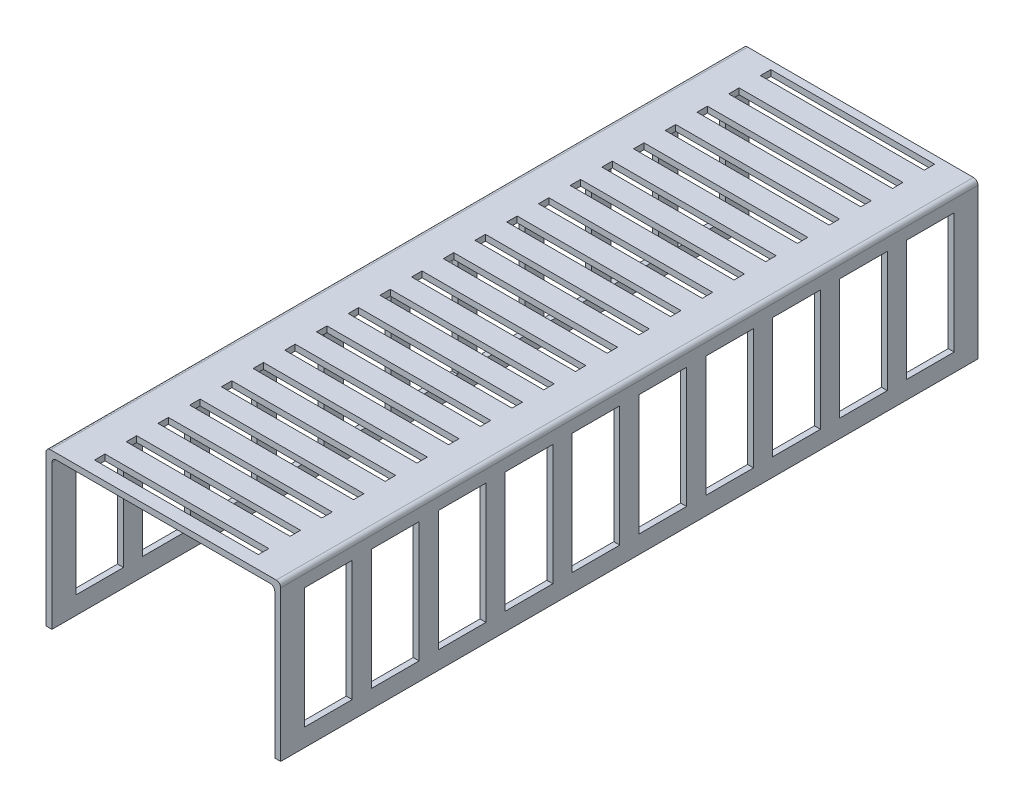
SolidWorks part; units mm, degrees
material "Nylon 101"
ref_plane "Front Plane" through (0, 0, 0) normal (0, 0, 1) x (1, 0, 0)
ref_plane "Top Plane" through (0, 0, 0) normal (0, 1, 0) x (1, 0, 0)
ref_plane "Right Plane" through (0, 0, 0) normal (1, 0, 0) x (0, 0, -1)
sketch "Sketch2" plane through (0, 16100.0493, 0) normal (0, 1, 0) x (1, 0, 0)
  line L0 (-34.7, 120.7548) -> (-34.7, 117.2548)
  line L5 (-34.7, 117.2548) -> (20.3, 117.2548)
  line L6 (-34.7, 120.7548) -> (20.3, 120.7548)
  line L7 (20.3, 120.7548) -> (20.3, 117.2548)
  line L9 (-46.6, 134.05) -> (32.2, 134.05)
  line L10 (-46.6, 134.05) -> (-46.6, -100.05)
  line L11 (-46.6, -100.05) -> (32.2, -100.05)
  line L12 (32.2, 134.05) -> (32.2, -100.05)
  line L13 (-49.2, -101.05) -> (34.8, -101.05) construction
  line L17 (33.2179, 129.65) -> (30.05, 129.65) construction
  line L18 (30.05, 124.75) -> (30.05, 130.7) construction
  line L19 (-38.7, 139.3) -> (-38.7, 131.4) construction
  line L20 (-34.7, 131.4) -> (20.3, 131.4)
  line L21 (-34.7, 131.4) -> (-34.7, 127.9)
  line L22 (-34.7, 127.9) -> (20.3, 127.9)
  line L23 (20.3, 131.4) -> (20.3, 127.9)
  line L24 (-34.7, 131.4) -> (20.3, 127.9) construction
  line L25 (-34.7, 127.9) -> (20.3, 131.4) construction
  line L26 (-34.7, 110.1095) -> (-34.7, 106.6095)
  line L27 (-34.7, 106.6095) -> (20.3, 106.6095)
  line L28 (-34.7, 110.1095) -> (20.3, 110.1095)
  line L29 (20.3, 110.1095) -> (20.3, 106.6095)
  line L30 (-34.7, 99.4643) -> (-34.7, 95.9643)
  line L31 (-34.7, 95.9643) -> (20.3, 95.9643)
  line L32 (-34.7, 99.4643) -> (20.3, 99.4643)
  line L33 (20.3, 99.4643) -> (20.3, 95.9643)
  line L34 (-34.7, 88.819) -> (-34.7, 85.319)
  line L35 (-34.7, 85.319) -> (20.3, 85.319)
  line L36 (-34.7, 88.819) -> (20.3, 88.819)
  line L37 (20.3, 88.819) -> (20.3, 85.319)
  line L38 (-34.7, 78.1738) -> (-34.7, 74.6738)
  line L39 (-34.7, 74.6738) -> (20.3, 74.6738)
  line L40 (-34.7, 78.1738) -> (20.3, 78.1738)
  line L41 (20.3, 78.1738) -> (20.3, 74.6738)
  line L42 (-34.7, 67.5286) -> (-34.7, 64.0286)
  line L43 (-34.7, 64.0286) -> (20.3, 64.0286)
  line L44 (-34.7, 67.5286) -> (20.3, 67.5286)
  line L45 (20.3, 67.5286) -> (20.3, 64.0286)
  line L46 (-34.7, 56.8833) -> (-34.7, 53.3833)
  line L47 (-34.7, 53.3833) -> (20.3, 53.3833)
  line L48 (-34.7, 56.8833) -> (20.3, 56.8833)
  line L49 (20.3, 56.8833) -> (20.3, 53.3833)
  line L50 (-34.7, 46.2381) -> (-34.7, 42.7381)
  line L51 (-34.7, 42.7381) -> (20.3, 42.7381)
  line L52 (-34.7, 46.2381) -> (20.3, 46.2381)
  line L53 (20.3, 46.2381) -> (20.3, 42.7381)
  line L54 (-34.7, 35.5929) -> (-34.7, 32.0929)
  line L55 (-34.7, 32.0929) -> (20.3, 32.0929)
  line L56 (-34.7, 35.5929) -> (20.3, 35.5929)
  line L57 (20.3, 35.5929) -> (20.3, 32.0929)
  line L58 (-34.7, 24.9476) -> (-34.7, 21.4476)
  line L59 (-34.7, 21.4476) -> (20.3, 21.4476)
  line L60 (-34.7, 24.9476) -> (20.3, 24.9476)
  line L61 (20.3, 24.9476) -> (20.3, 21.4476)
  line L62 (-34.7, 14.3024) -> (-34.7, 10.8024)
  line L63 (-34.7, 10.8024) -> (20.3, 10.8024)
  line L64 (-34.7, 14.3024) -> (20.3, 14.3024)
  line L65 (20.3, 14.3024) -> (20.3, 10.8024)
  line L66 (-34.7, 3.6571) -> (-34.7, 0.1571)
  line L67 (-34.7, 0.1571) -> (20.3, 0.1571)
  line L68 (-34.7, 3.6571) -> (20.3, 3.6571)
  line L69 (20.3, 3.6571) -> (20.3, 0.1571)
  line L70 (-34.7, -6.9881) -> (-34.7, -10.4881)
  line L71 (-34.7, -10.4881) -> (20.3, -10.4881)
  line L72 (-34.7, -6.9881) -> (20.3, -6.9881)
  line L73 (20.3, -6.9881) -> (20.3, -10.4881)
  line L74 (-34.7, -17.6333) -> (-34.7, -21.1333)
  line L75 (-34.7, -21.1333) -> (20.3, -21.1333)
  line L76 (-34.7, -17.6333) -> (20.3, -17.6333)
  line L77 (20.3, -17.6333) -> (20.3, -21.1333)
  line L78 (-34.7, -28.2786) -> (-34.7, -31.7786)
  line L79 (-34.7, -31.7786) -> (20.3, -31.7786)
  line L80 (-34.7, -28.2786) -> (20.3, -28.2786)
  line L81 (20.3, -28.2786) -> (20.3, -31.7786)
  line L82 (-34.7, -38.9238) -> (-34.7, -42.4238)
  line L83 (-34.7, -42.4238) -> (20.3, -42.4238)
  line L84 (-34.7, -38.9238) -> (20.3, -38.9238)
  line L85 (20.3, -38.9238) -> (20.3, -42.4238)
  line L86 (-34.7, -49.569) -> (-34.7, -53.069)
  line L87 (-34.7, -53.069) -> (20.3, -53.069)
  line L88 (-34.7, -49.569) -> (20.3, -49.569)
  line L89 (20.3, -49.569) -> (20.3, -53.069)
  line L90 (-34.7, -60.2143) -> (-34.7, -63.7143)
  line L91 (-34.7, -63.7143) -> (20.3, -63.7143)
  line L92 (-34.7, -60.2143) -> (20.3, -60.2143)
  line L93 (20.3, -60.2143) -> (20.3, -63.7143)
  line L94 (-34.7, -70.8595) -> (-34.7, -74.3595)
  line L95 (-34.7, -74.3595) -> (20.3, -74.3595)
  line L96 (-34.7, -70.8595) -> (20.3, -70.8595)
  line L97 (20.3, -70.8595) -> (20.3, -74.3595)
  line L98 (-34.7, -81.5048) -> (-34.7, -85.0048)
  line L99 (-34.7, -85.0048) -> (20.3, -85.0048)
  line L100 (-34.7, -81.5048) -> (20.3, -81.5048)
  line L101 (20.3, -81.5048) -> (20.3, -85.0048)
  line L102 (-34.7, -92.15) -> (-34.7, -95.65)
  line L103 (-34.7, -95.65) -> (20.3, -95.65)
  line L104 (-34.7, -92.15) -> (20.3, -92.15)
  line L105 (20.3, -92.15) -> (20.3, -95.65)
  line L107 (-49.2, 135.05) -> (34.8, 135.05) construction
  line L108 (-47.2, -100.65) -> (-47.2, 134.65) construction
  line L109 (32.8, -100.65) -> (32.8, 134.65) construction
  point P21 (-7.2, 129.65)
  dimension "D1" = 1
  dimension "D2" = 1
  dimension "D3" = 0.6
  dimension "D4" = 0.6
  dimension "D5" = 4
  dimension "D6" = 3.5
  dimension "D8" = 4.4
  dimension "D9" = 4.4
  dimension "D7" = 22
extrude "Boss-Extrude1" add sketch "Sketch2" along normal blind 2
sketch "Sketch3" plane through (0, 16100.0493, 0) normal (0, -1, 0) x (1, 0, 0)
  line L0 (32.2, -134.05) -> (-46.6, -134.05) construction
  line L1 (-46.6, 100.05) -> (-44.6, 100.05)
  line L2 (-46.6, 100.05) -> (-46.6, -134.05)
  line L3 (-46.6, -134.05) -> (-44.6, -134.05)
  line L4 (-44.6, 100.05) -> (-44.6, -134.05)
  line L5 (-7.2, 100.05) -> (-7.2, -2.7153) construction
  line L6 (-46.6, 100.05) -> (32.2, 100.05) construction
  line L7 (30.2, 100.05) -> (30.2, -134.05)
  line L8 (32.2, -134.05) -> (30.2, -134.05)
  line L9 (32.2, 100.05) -> (32.2, -134.05)
  line L10 (32.2, 100.05) -> (30.2, 100.05)
  dimension "D1" = 2
extrude "Boss-Extrude2" add sketch "Sketch3" along normal blind 50
fillet "Fillet1" radius 1.5 4 edges at (-44.6, 16100.0493, -17) (-46.6, 16102.0493, -17) (30.2, 16100.0493, -17) (32.2, 16102.0493, -17)
sketch "Sketch4" plane through (32.2, 0, 0) normal (1, 0, 0) x (0, 0, -1)
  line L0 (-100.05, 16100.5493) -> (-100.05, 16050.0493) construction
  line L1 (-92.05, 16096.5493) -> (-76.05, 16096.5493)
  line L2 (-92.05, 16096.5493) -> (-92.05, 16056.0493)
  line L3 (-92.05, 16056.0493) -> (-76.05, 16056.0493)
  line L4 (-76.05, 16096.5493) -> (-76.05, 16056.0493)
  line L5 (134.05, 16100.5493) -> (-100.05, 16100.5493) construction
  line L6 (134.05, 16050.0493) -> (-100.05, 16050.0493) construction
  line L7 (-69.5944, 16096.5493) -> (-53.5944, 16096.5493)
  line L8 (-69.5944, 16096.5493) -> (-69.5944, 16056.0493)
  line L9 (-69.5944, 16056.0493) -> (-53.5944, 16056.0493)
  line L10 (-53.5944, 16096.5493) -> (-53.5944, 16056.0493)
  line L11 (-47.1389, 16096.5493) -> (-31.1389, 16096.5493)
  line L12 (-47.1389, 16096.5493) -> (-47.1389, 16056.0493)
  line L13 (-47.1389, 16056.0493) -> (-31.1389, 16056.0493)
  line L14 (-31.1389, 16096.5493) -> (-31.1389, 16056.0493)
  line L15 (-24.6833, 16096.5493) -> (-8.6833, 16096.5493)
  line L16 (-24.6833, 16096.5493) -> (-24.6833, 16056.0493)
  line L17 (-24.6833, 16056.0493) -> (-8.6833, 16056.0493)
  line L18 (-8.6833, 16096.5493) -> (-8.6833, 16056.0493)
  line L19 (-2.2278, 16096.5493) -> (13.7722, 16096.5493)
  line L20 (-2.2278, 16096.5493) -> (-2.2278, 16056.0493)
  line L21 (-2.2278, 16056.0493) -> (13.7722, 16056.0493)
  line L22 (13.7722, 16096.5493) -> (13.7722, 16056.0493)
  line L23 (20.2278, 16096.5493) -> (36.2278, 16096.5493)
  line L24 (20.2278, 16096.5493) -> (20.2278, 16056.0493)
  line L25 (20.2278, 16056.0493) -> (36.2278, 16056.0493)
  line L26 (36.2278, 16096.5493) -> (36.2278, 16056.0493)
  line L27 (42.6833, 16096.5493) -> (58.6833, 16096.5493)
  line L28 (42.6833, 16096.5493) -> (42.6833, 16056.0493)
  line L29 (42.6833, 16056.0493) -> (58.6833, 16056.0493)
  line L30 (58.6833, 16096.5493) -> (58.6833, 16056.0493)
  line L31 (65.1389, 16096.5493) -> (81.1389, 16096.5493)
  line L32 (65.1389, 16096.5493) -> (65.1389, 16056.0493)
  line L33 (65.1389, 16056.0493) -> (81.1389, 16056.0493)
  line L34 (81.1389, 16096.5493) -> (81.1389, 16056.0493)
  line L35 (87.5944, 16096.5493) -> (103.5944, 16096.5493)
  line L36 (87.5944, 16096.5493) -> (87.5944, 16056.0493)
  line L37 (87.5944, 16056.0493) -> (103.5944, 16056.0493)
  line L38 (103.5944, 16096.5493) -> (103.5944, 16056.0493)
  line L39 (110.05, 16096.5493) -> (126.05, 16096.5493)
  line L40 (110.05, 16096.5493) -> (110.05, 16056.0493)
  line L41 (110.05, 16056.0493) -> (126.05, 16056.0493)
  line L42 (126.05, 16096.5493) -> (126.05, 16056.0493)
  line L43 (134.05, 16100.5493) -> (134.05, 16050.0493) construction
  dimension "D1" = 8
  dimension "D2" = 4
  dimension "D3" = 6
  dimension "D4" = 16
  dimension "D6" = 8
  dimension "D5" = 10
extrude "Cut-Extrude1" cut sketch "Sketch4" against normal through all
